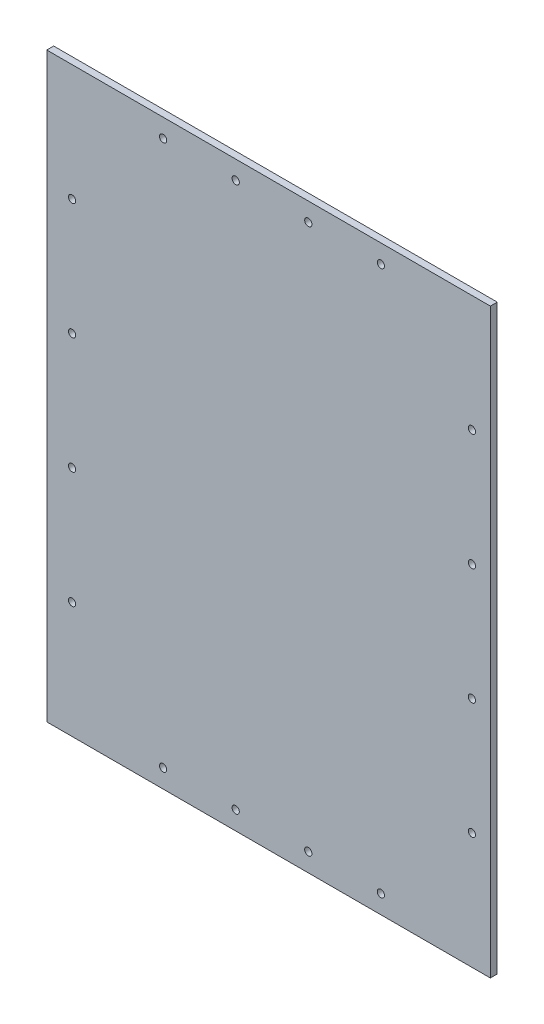
SolidWorks part; units mm, degrees
ref_plane "前基準面" through (0, 0, 0) normal (0, 0, 1) x (1, 0, 0)
ref_plane "上基準面" through (0, 0, 0) normal (0, 1, 0) x (1, 0, 0)
ref_plane "右基準面" through (0, 0, 0) normal (1, 0, 0) x (0, 0, -1)
sketch "草圖1" plane through (0, 0, 0) normal (0, 0, 1) x (1, 0, 0)
  line L1 (152.775, -202.775) -> (-152.775, -202.775)
  line L2 (152.775, -202.775) -> (152.775, 202.775)
  line L3 (152.775, 202.775) -> (-152.775, 202.775)
  line L4 (-152.775, -202.775) -> (-152.775, 202.775)
  line L5 (152.775, -202.775) -> (-152.775, 202.775) construction
  line L6 (152.775, 202.775) -> (-152.775, -202.775) construction
  point P0 (0, 0)
  dimension "D1" = 305.55
  dimension "D2" = 405.55
extrude "填料-伸長1" add sketch "草圖1" along normal blind 4.75
sketch "草圖3" plane through (0, 0, 4.75) normal (0, 0, 1) x (1, 0, 0)
  line L0 (152.775, 202.775) -> (140.075, 202.775) construction
  line L1 (152.775, 202.775) -> (-152.775, 202.775) construction
  line L2 (140.075, 202.775) -> (140.075, 198.025) construction
  line L3 (140.075, 198.025) -> (140.075, 117.865) construction
  line L4 (140.075, 117.865) -> (140.075, 37.705) construction
  line L5 (140.075, 37.705) -> (140.075, -42.455) construction
  line L6 (140.075, -42.455) -> (140.075, -122.615) construction
  circle A0 centre (140.075, 37.705) radius 2.5
  circle A1 centre (140.075, 117.865) radius 2.5
  circle A2 centre (140.075, -42.455) radius 2.5
  circle A3 centre (140.075, -122.615) radius 2.5
  dimension "D7" = 5
  dimension "D8" = 5
  dimension "D9" = 5
  dimension "D10" = 5
  dimension "D1" = 12.7
  dimension "D2" = 4.75
  dimension "D3" = 80.16
  dimension "D4" = 80.16
  dimension "D5" = 80.16
  dimension "D6" = 80.16
extrude "除料-伸長1" cut sketch "草圖3" against normal blind 10
sketch "草圖5" plane through (0, 0, 4.75) normal (0, 0, 1) x (1, 0, 0)
  line L0 (-152.775, 202.775) -> (-148.025, 202.775) construction
  line L1 (152.775, 202.775) -> (-152.775, 202.775) construction
  line L2 (-148.025, 202.775) -> (-135.325, 202.775) construction
  line L3 (-135.325, 202.775) -> (-135.325, 198.025) construction
  line L4 (-135.325, 198.025) -> (-135.325, 117.865) construction
  line L5 (-135.325, 117.865) -> (-135.325, 37.705) construction
  line L6 (-135.325, 37.705) -> (-135.325, -42.455) construction
  line L7 (-135.325, -42.455) -> (-135.325, -122.615) construction
  circle A0 centre (-135.325, -122.615) radius 2.5
  circle A1 centre (-135.325, -42.455) radius 2.5
  circle A2 centre (-135.325, 37.705) radius 2.5
  circle A3 centre (-135.325, 117.865) radius 2.5
  dimension "D8" = 5
  dimension "D9" = 5
  dimension "D10" = 5
  dimension "D11" = 5
  dimension "D1" = 4.75
  dimension "D2" = 12.7
  dimension "D3" = 4.75
  dimension "D4" = 80.16
  dimension "D5" = 80.16
  dimension "D6" = 80.16
  dimension "D7" = 80.16
extrude "除料-伸長3" cut sketch "草圖5" against normal blind 10
sketch "草圖6" plane through (0, 0, 0) normal (0, 0, -1) x (-1, 0, 0)
  line L0 (-152.775, 202.775) -> (-127.375, 202.775) construction
  line L1 (-152.775, 202.775) -> (152.775, 202.775) construction
  line L2 (-127.375, 202.775) -> (-127.375, 190.075) construction
  line L3 (-127.375, 190.075) -> (-127.375, 185.325) construction
  line L4 (-127.375, 185.325) -> (-77.375, 185.325) construction
  line L5 (-77.375, 185.325) -> (-27.375, 185.325) construction
  line L6 (-27.375, 185.325) -> (22.625, 185.325) construction
  line L7 (22.625, 185.325) -> (72.625, 185.325) construction
  circle A0 centre (22.625, 185.325) radius 2.5
  circle A1 centre (72.625, 185.325) radius 2.5
  circle A2 centre (-77.375, 185.325) radius 2.5
  circle A3 centre (-27.375, 185.325) radius 2.5
  dimension "D8" = 5
  dimension "D9" = 5
  dimension "D10" = 5
  dimension "D11" = 5
  dimension "D1" = 25.4
  dimension "D2" = 12.7
  dimension "D3" = 4.75
  dimension "D4" = 50
  dimension "D5" = 50
  dimension "D6" = 50
  dimension "D7" = 50
extrude "除料-伸長4" cut sketch "草圖6" against normal blind 10
sketch "草圖7" plane through (0, 0, 0) normal (0, 0, -1) x (-1, 0, 0)
  line L0 (-152.775, -202.775) -> (-152.775, -190.075) construction
  line L1 (-152.775, -202.775) -> (-152.775, 202.775) construction
  line L2 (-152.775, -190.075) -> (-127.375, -190.075) construction
  line L3 (-127.375, -190.075) -> (-77.375, -190.075) construction
  line L4 (-77.375, -190.075) -> (-27.375, -190.075) construction
  line L5 (-27.375, -190.075) -> (22.625, -190.075) construction
  line L6 (22.625, -190.075) -> (72.625, -190.075) construction
  circle A0 centre (-77.375, -190.075) radius 2.5
  circle A1 centre (-27.375, -190.075) radius 2.5
  circle A2 centre (22.625, -190.075) radius 2.5
  circle A3 centre (72.625, -190.075) radius 2.5
  dimension "D7" = 5
  dimension "D8" = 5
  dimension "D9" = 5
  dimension "D10" = 5
  dimension "D1" = 12.7
  dimension "D2" = 25.4
  dimension "D3" = 50
  dimension "D4" = 50
  dimension "D5" = 50
  dimension "D6" = 50
extrude "除料-伸長5" cut sketch "草圖7" against normal blind 10
sketch "草圖8" plane through (0, 0, 4.75) normal (0, 0, 1) x (1, 0, 0)
  line L0 (152.775, -202.775) -> (152.775, 202.775) construction
  line L1 (-152.775, 202.775) -> (152.775, 202.775)
  line L2 (-152.775, 202.775) -> (-152.775, 198.025)
  line L3 (-152.775, 198.025) -> (152.775, 198.025)
  line L4 (152.775, 202.775) -> (152.775, 198.025)
  dimension "D1" = 4.75
split "分割1" trim tools "草圖8" bodies to split 106 resulting bodies 107
